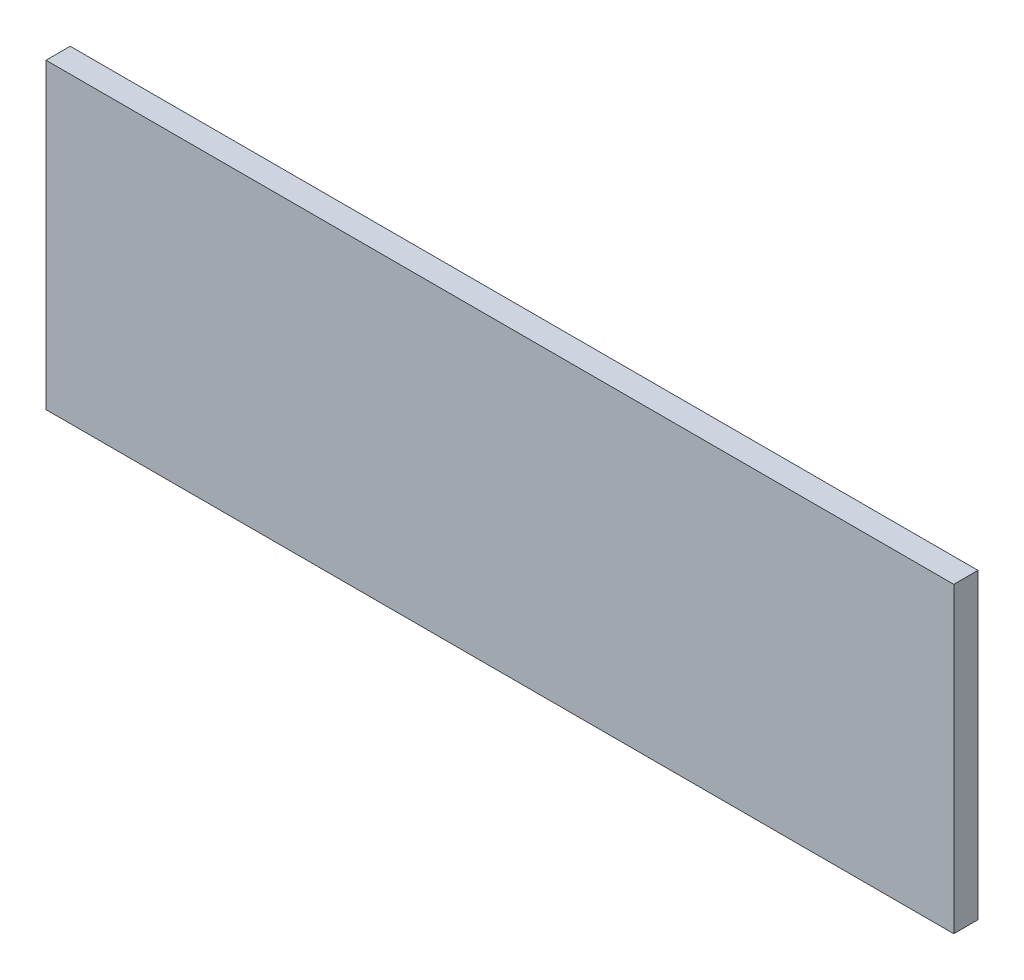
SolidWorks part; units mm, degrees
ref_plane "Front Plane" through (0, 0, 0) normal (0, 0, 1) x (1, 0, 0)
ref_plane "Top Plane" through (0, 0, 0) normal (0, 1, 0) x (1, 0, 0)
ref_plane "Right Plane" through (0, 0, 0) normal (1, 0, 0) x (0, 0, -1)
sketch "Sketch1" plane through (0, 0, 0) normal (1, 0, 0) x (0, 0, -1)
  line L1 (-2, -25) -> (2, -25)
  line L2 (-2, -25) -> (-2, 25)
  line L3 (-2, 25) -> (2, 25)
  line L4 (2, -25) -> (2, 25)
  line L5 (-2, -25) -> (2, 25) construction
  line L6 (-2, 25) -> (2, -25) construction
  point P0 (0, 0)
  dimension "D1" = 50
  dimension "D2" = 4
extrude "Boss-Extrude1" add sketch "Sketch1" along normal mid plane 150
